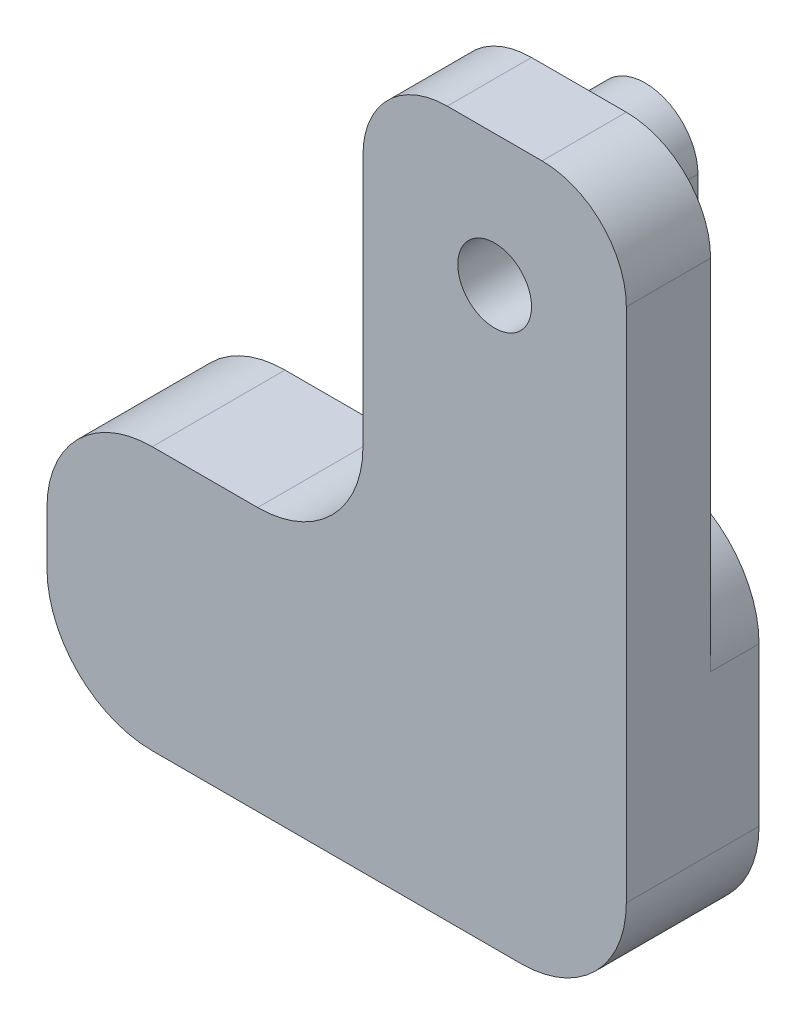
SolidWorks part; units mm, degrees
ref_plane "Front Plane" through (0, 0, 0) normal (0, 0, 1) x (1, 0, 0)
ref_plane "Top Plane" through (0, 0, 0) normal (0, 1, 0) x (1, 0, 0)
ref_plane "Right Plane" through (0, 0, 0) normal (1, 0, 0) x (0, 0, -1)
sketch "Sketch1" plane through (0, 0, 0) normal (0, 0, 1) x (1, 0, 0)
  line L0 (0, 4.5) -> (0, -4.5) construction
  line L1 (5, 4.5) -> (5, -4.5)
  line L2 (-5, 4.5) -> (-5, -4.5)
  arc A0 (5, 4.5) -> (-5, 4.5) centre (0, 4.5) ccw
  arc A1 (-5, -4.5) -> (5, -4.5) centre (0, -4.5) ccw
  point P2 (0, 0)
  point P8 (0, 9.5)
  point P9 (0, -9.5)
  dimension "D1" = 10
  dimension "D2" = 19
extrude "Boss-Extrude1" add sketch "Sketch1" along normal blind 6.3 contours L2 A1 L1 A0
sketch "Sketch2" plane through (0, 0, 6.3) normal (0, 0, 1) x (1, 0, 0)
  line L1 (-4.5, 12.5) -> (4.5, 12.5)
  line L2 (-12.5, 4.5) -> (-12.5, -4.5)
  line L3 (-4.5, -12.5) -> (4.5, -12.5)
  line L4 (12.5, 4.5) -> (12.5, -4.5)
  line L5 (-12.5, 12.5) -> (12.5, -12.5) construction
  line L6 (-12.5, -12.5) -> (12.5, 12.5) construction
  arc A0 (-4.5, 12.5) -> (-12.5, 4.5) centre (-4.5, 4.5) ccw
  arc A1 (-12.5, -4.5) -> (-4.5, -12.5) centre (-4.5, -4.5) ccw
  arc A2 (4.5, -12.5) -> (12.5, -4.5) centre (4.5, -4.5) ccw
  arc A3 (4.5, 12.5) -> (12.5, 4.5) centre (4.5, 4.5) cw
  point P0 (0, 0)
  dimension "D1" = 8
  dimension "D2" = 25
  dimension "D3" = 25
extrude "Boss-Extrude2" add sketch "Sketch2" along normal blind 8
sketch "Sketch3" plane through (0, 0, 14.3) normal (0, 0, 1) x (1, 0, 0)
  circle A0 centre (0, 0) radius 3.5
  dimension "D1" = 7
extrude "Cut-Extrude1" cut sketch "Sketch3" against normal blind 8
sketch "Sketch4" plane through (0, 0, 14.3) normal (0, 0, 1) x (1, 0, 0)
  line L0 (-12.5, -4.5) -> (-12.5, -54.5)
  line L1 (-12.5, -54.5) -> (12.5, -54.5)
  line L2 (12.5, -54.5) -> (12.5, -4.5)
  line L3 (-4.5, -12.5) -> (4.5, -12.5) construction
  line L4 (-4.5, -12.5) -> (4.5, -12.5)
  arc A0 (-5, -4.5) -> (5, -4.5) centre (0, -4.5) ccw construction
  arc A1 (-5, -4.5) -> (5, -4.5) centre (0, -4.5) ccw construction
  arc A2 (4.5, -12.5) -> (12.5, -4.5) centre (4.5, -4.5) ccw construction
  arc A3 (-12.5, -4.5) -> (-4.5, -12.5) centre (-4.5, -4.5) ccw construction
  arc A4 (4.5, -12.5) -> (12.5, -4.5) centre (4.5, -4.5) ccw
  arc A5 (-12.5, -4.5) -> (-4.5, -12.5) centre (-4.5, -4.5) ccw
  point P9 (0, -9.5)
  dimension "D1" = 45
extrude "Boss-Extrude3" add sketch "Sketch4" against normal up to surface (8 mm away) up to face at (0, 0, 6.3)
sketch "Sketch5" plane through (0, 0, 14.3) normal (0, 0, 1) x (1, 0, 0)
  line L0 (-12.5, -54.5) -> (-42.5, -54.5)
  line L1 (-42.5, -54.5) -> (-42.5, -29.5)
  line L2 (-42.5, -29.5) -> (-12.5, -29.5)
  line L3 (-12.5, 4.5) -> (-12.5, -54.5) construction
  line L4 (-12.5, -29.5) -> (-12.5, -54.5)
  line L5 (-12.5, -54.5) -> (12.5, -54.5) construction
  dimension "D1" = 30
extrude "Boss-Extrude4" add sketch "Sketch5" against normal up to surface (8 mm away) up to face at (0, -11.9477, 6.3)
fillet "Fillet1" radius 10 4 edges at (12.5, -54.5, 10.3) (-42.5, -54.5, 10.3) (-12.5, -29.5, 10.3) (-42.5, -29.5, 10.3)
sketch "Sketch6" plane through (0, 0, 6.3) normal (0, 0, -1) x (-1, 0, 0)
  line L0 (-2.5, -19.5) -> (5.1795, -19.5)
  line L6 (-12.5, 4.5) -> (-12.5, -44.5)
  line L7 (-2.5, -54.5) -> (32.5, -54.5)
  line L8 (42.5, -44.5) -> (42.5, -39.5)
  line L9 (32.5, -29.5) -> (22.5, -29.5)
  line L10 (12.5, -19.5) -> (12.5, 4.5)
  line L11 (4.5, 12.5) -> (-4.5, 12.5)
  line L12 (-12.5, -29.5) -> (-12.5, -44.5)
  line L13 (-2.5, -54.5) -> (32.5, -54.5)
  line L14 (42.5, -44.5) -> (42.5, -39.5)
  line L15 (32.5, -29.5) -> (22.5, -29.5)
  arc A1 (-2.5, -19.5) -> (-12.5, -29.5) centre (-2.5, -29.5) ccw
  arc A2 (5.1795, -19.5) -> (13.8397, -24.5) centre (5.1795, -29.5) cw
  arc A6 (-12.5, -44.5) -> (-2.5, -54.5) centre (-2.5, -44.5) ccw
  arc A7 (32.5, -54.5) -> (42.5, -44.5) centre (32.5, -44.5) ccw
  arc A8 (42.5, -39.5) -> (32.5, -29.5) centre (32.5, -39.5) ccw
  arc A9 (12.5, -19.5) -> (22.5, -29.5) centre (22.5, -19.5) ccw
  arc A10 (12.5, 4.5) -> (4.5, 12.5) centre (4.5, 4.5) ccw
  arc A11 (-4.5, 12.5) -> (-12.5, 4.5) centre (-4.5, 4.5) ccw
  arc A12 (-12.5, -44.5) -> (-2.5, -54.5) centre (-2.5, -44.5) ccw
  arc A13 (32.5, -54.5) -> (42.5, -44.5) centre (32.5, -44.5) ccw
  arc A14 (42.5, -39.5) -> (32.5, -29.5) centre (32.5, -39.5) ccw
  arc A15 (13.8397, -24.5) -> (22.5, -29.5) centre (22.5, -19.5) ccw
  dimension "D2" = 10
  dimension "D1" = 0
extrude "Boss-Extrude5" add sketch "Sketch6" along normal blind 4.6
